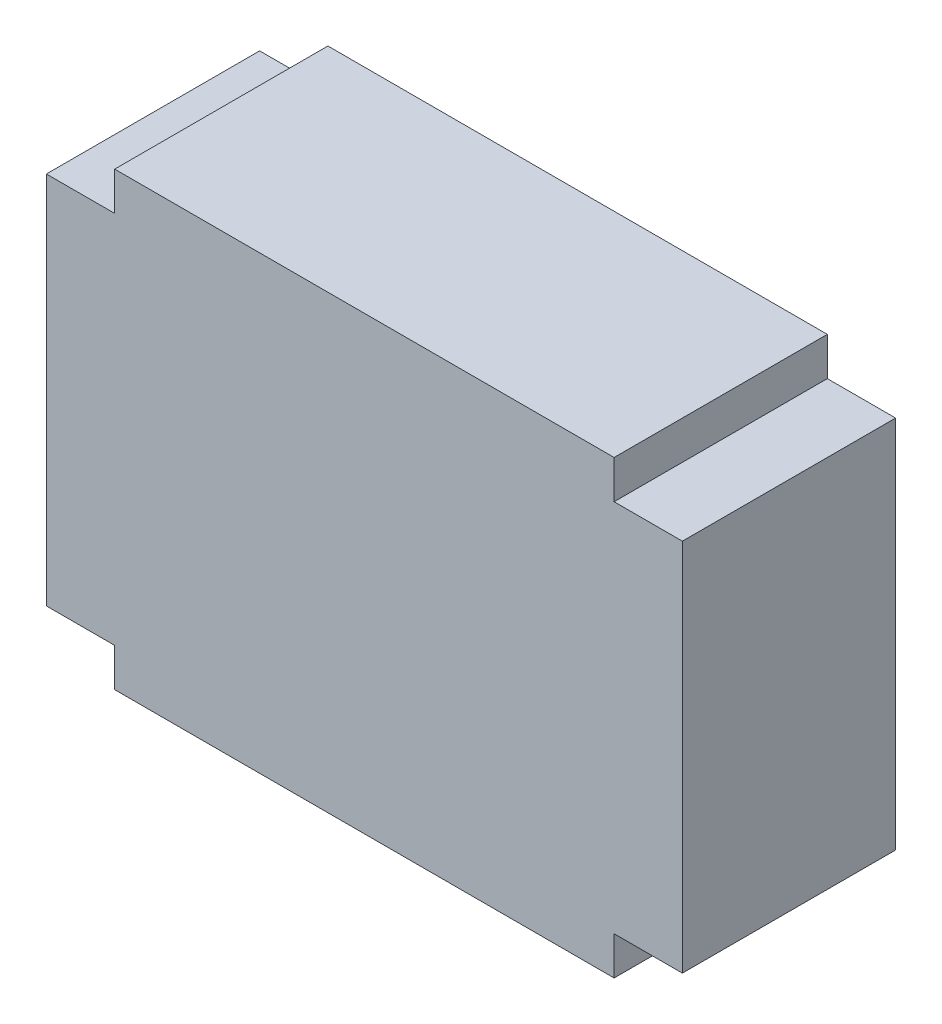
SolidWorks part; units mm, degrees
ref_plane "前视基准面" through (0, 0, 0) normal (0, 0, 1) x (1, 0, 0)
ref_plane "上视基准面" through (0, 0, 0) normal (0, 1, 0) x (1, 0, 0)
ref_plane "右视基准面" through (0, 0, 0) normal (1, 0, 0) x (0, 0, -1)
sketch "草图1" plane through (0, 0, 0) normal (0, 0, 1) x (1, 0, 0)
  line L0 (-1.7, 1) -> (-1.335, 1)
  line L1 (-1.335, 1) -> (-1.335, 1.205)
  line L2 (-1.335, 1.205) -> (1.335, 1.205)
  line L3 (1.335, 1.205) -> (1.335, 1)
  line L4 (1.335, 1) -> (1.7, 1)
  line L5 (1.7, 1) -> (1.7, -1)
  line L6 (1.7, -1) -> (1.335, -1)
  line L7 (1.335, -1) -> (1.335, -1.205)
  line L8 (1.335, -1.205) -> (-1.335, -1.205)
  line L9 (-1.335, -1.205) -> (-1.335, -1)
  line L10 (-1.335, -1) -> (-1.7, -1)
  line L11 (-1.7, -1) -> (-1.7, 1)
extrude "Component_Outline" add sketch "草图1" along normal blind 1.14 separate body
sketch3d "3D草图1"
  line L0 (0, 0, 0) -> (1, 0, 0)
  line L1 (0, 0, 0) -> (0, 1, 0)
  line L2 (0, 0, 0) -> (0, 0, 1)
  point P0 (0, 0, 0)
